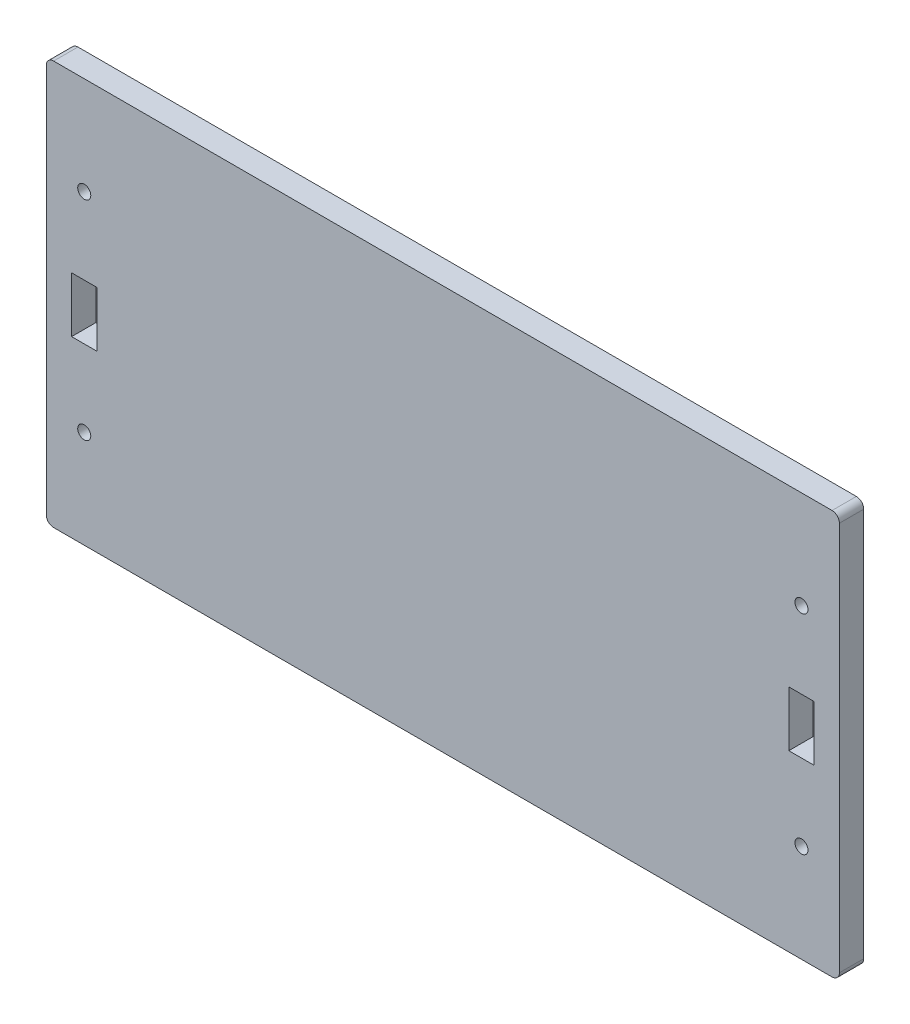
SolidWorks part; units mm, degrees
ref_plane "Front Plane" through (0, 0, 0) normal (0, 0, 1) x (1, 0, 0)
ref_plane "Top Plane" through (0, 0, 0) normal (0, 1, 0) x (1, 0, 0)
ref_plane "Right Plane" through (0, 0, 0) normal (1, 0, 0) x (0, 0, -1)
sketch "Model" plane through (0, 0, 0) normal (0, 0, 1) x (1, 0, 0)
  line L0 (201.54, 47.3262) -> (208.4, 47.3262)
  line L1 (208.4, 47.3262) -> (208.4, 62.3262)
  line L2 (208.4, 62.3262) -> (201.54, 62.3262)
  line L3 (201.54, 62.3262) -> (201.54, 47.3262)
  line L4 (13.74, 47.3262) -> (13.74, 62.3262)
  line L5 (13.74, 62.3262) -> (6.88, 62.3262)
  line L6 (6.88, 62.3262) -> (6.88, 47.3262)
  line L7 (6.88, 47.3262) -> (13.74, 47.3262)
  line L8 (213.28, 109.66) -> (2, 109.66)
  line L9 (215.28, 2) -> (215.28, 107.66)
  line L10 (2, 0) -> (213.28, 0)
  line L11 (0, 107.66) -> (0, 2)
  circle A0 centre (10.31, 83.1012) radius 1.775
  circle A1 centre (10.31, 26.5512) radius 1.775
  circle A2 centre (204.97, 26.5512) radius 1.775
  circle A3 centre (204.97, 83.1012) radius 1.775
  arc A4 (213.28, 0) -> (215.28, 2) centre (213.28, 2) ccw
  arc A5 (0, 2) -> (2, 0) centre (2, 2) ccw
  arc A6 (2, 109.66) -> (0, 107.66) centre (2, 107.66) ccw
  arc A7 (215.28, 107.66) -> (213.28, 109.66) centre (213.28, 107.66) ccw
extrude "Boss-Extrude1" add sketch "Model" along normal blind 6.6
